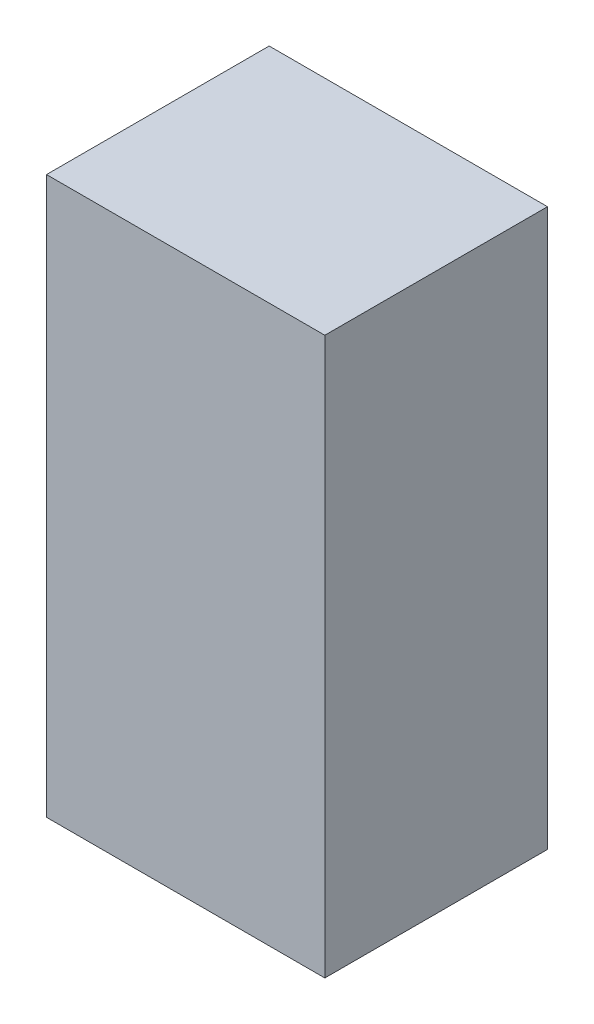
SolidWorks part; units mm, degrees
ref_plane "Front Plane" through (0, 0, 0) normal (1, 0, 0) x (0, 1, 0)
ref_plane "Top Plane" through (0, 0, 0) normal (0, 0, 1) x (0, 1, 0)
ref_plane "Right Plane" through (0, 0, 0) normal (0, 1, 0) x (-1, 0, 0)
sketch "Sketch1" plane through (0, 0, 0) normal (0, 0, 1) x (0, 1, 0)
  line L1 (-75, -37.5) -> (75, -37.5)
  line L2 (-75, -37.5) -> (-75, 37.5)
  line L3 (-75, 37.5) -> (75, 37.5)
  line L4 (75, -37.5) -> (75, 37.5)
  line L5 (-75, -37.5) -> (75, 37.5) construction
  line L6 (-75, 37.5) -> (75, -37.5) construction
  point P0 (0, 0)
  dimension "D1" = 150
  dimension "D2" = 75
extrude "Boss-Extrude1" add sketch "Sketch1" along normal blind 60
